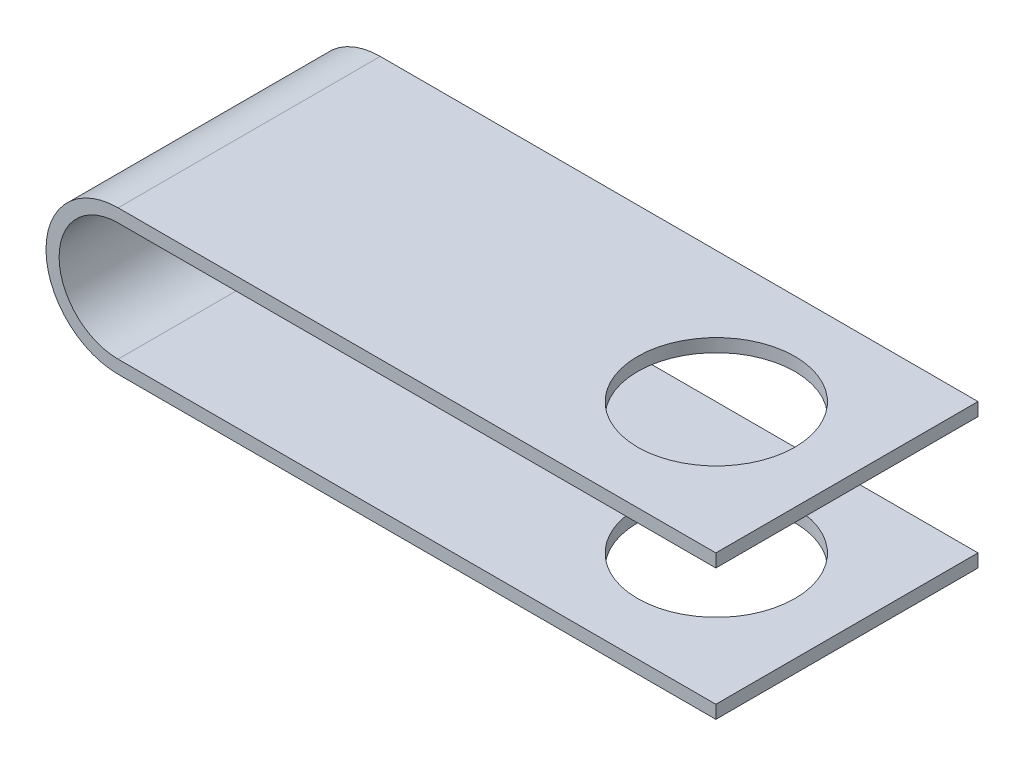
SolidWorks part; units mm, degrees
ref_plane "Front Plane" through (0, 0, 0) normal (0, 0, 1) x (1, 0, 0)
ref_plane "Top Plane" through (0, 0, 0) normal (0, 1, 0) x (1, 0, 0)
ref_plane "Right Plane" through (0, 0, 0) normal (1, 0, 0) x (0, 0, -1)
sketch "Sketch2" plane through (0, 0, 0) normal (0, 0, 1) x (1, 0, 0)
  line L0 (0, 0) -> (-57.912, 0)
  line L1 (0, 12.7) -> (-57.912, 12.7)
  line L2 (0, 0) -> (-57.912, 0)
  line L3 (0, 13.97) -> (-57.912, 13.97)
  line L4 (0, 1.27) -> (-57.912, 1.27)
  line L5 (0, 13.97) -> (0, 12.7)
  line L6 (0, 1.27) -> (0, 0)
  arc A0 (-57.912, 1.27) -> (-57.912, 12.7) centre (-57.912, 6.985) cw
  arc A1 (-57.912, 0) -> (-57.912, 13.97) centre (-57.912, 6.985) cw
  dimension "D1" = 57.912
  dimension "D2" = 12.7
  dimension "D3" = 12.7
  dimension "D4" = 1.27
  dimension "D5" = 1.27
extrude "Boss-Extrude1" add sketch "Sketch2" along normal blind 25.4 contours A1 L0 L6 L4 A0 L1 L5 L3
sketch "Sketch3" plane through (0, 13.97, 0) normal (0, 1, 0) x (1, 0, 0)
  circle A0 centre (-12.6571, -12.7) radius 7.62
  dimension "D1" = 15.24
extrude "Cut-Extrude1" cut sketch "Sketch3" against normal blind 25.4
